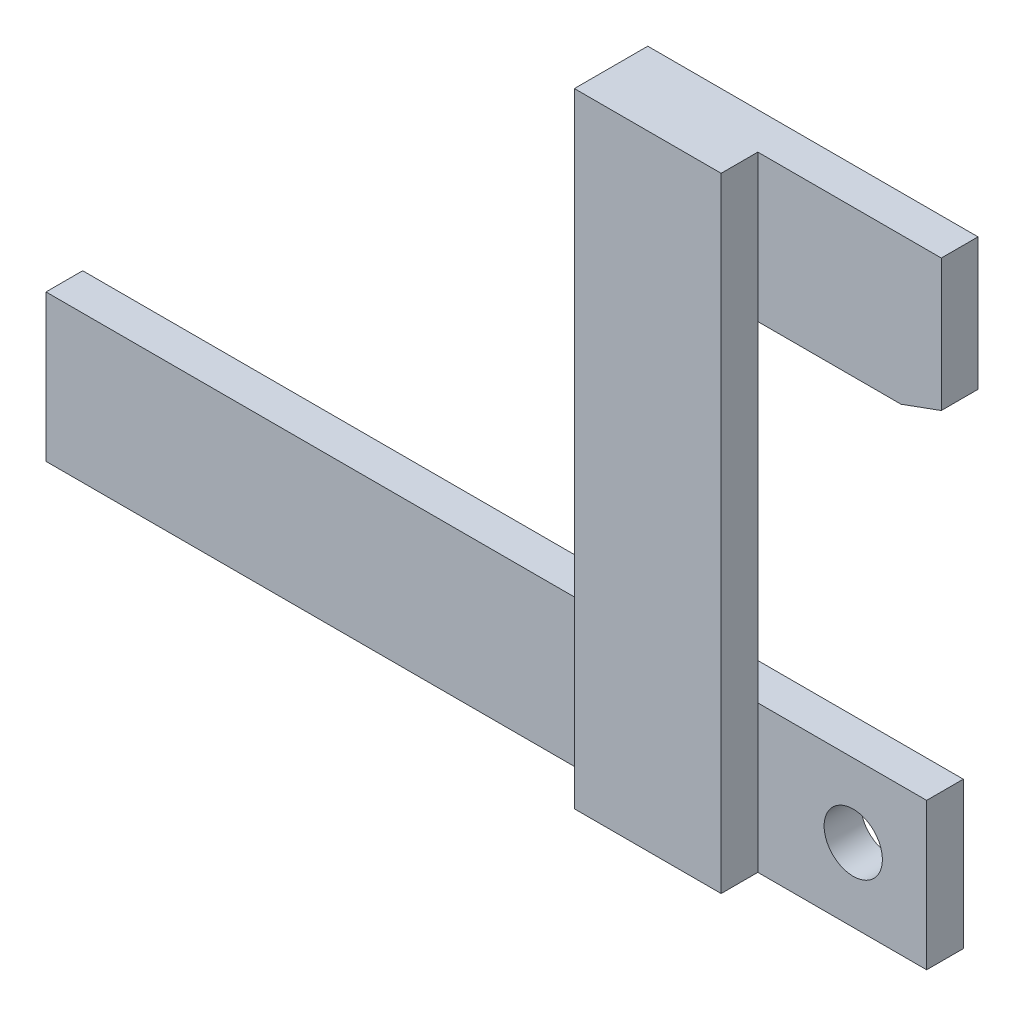
SolidWorks part; units mm, degrees
ref_plane "Front Plane" through (0, 0, 0) normal (0, 0, 1) x (1, 0, 0)
ref_plane "Top Plane" through (0, 0, 0) normal (0, 1, 0) x (1, 0, 0)
ref_plane "Right Plane" through (0, 0, 0) normal (1, 0, 0) x (0, 0, -1)
sketch "Sketch1" plane through (0, 0, 0) normal (0, 0, 1) x (1, 0, 0)
  line L1 (-76.2, -12.7) -> (76.2, -12.7)
  line L2 (-76.2, -12.7) -> (-76.2, 12.7)
  line L3 (-76.2, 12.7) -> (76.2, 12.7)
  line L4 (76.2, -12.7) -> (76.2, 12.7)
  line L5 (-76.2, -12.7) -> (76.2, 12.7) construction
  line L6 (-76.2, 12.7) -> (76.2, -12.7) construction
  point P0 (0, 0)
  dimension "D1" = 25.4
  dimension "D2" = 152.4
extrude "Extrude1" add sketch "Sketch1" along normal blind 6.35
sketch "Sketch2" plane through (0, 0, 6.35) normal (0, 0, 1) x (1, 0, 0)
  line L0 (-76.2, -12.7) -> (76.2, -12.7) construction
  line L1 (46.99, -12.7) -> (21.59, -12.7)
  line L2 (46.99, -12.7) -> (46.99, 95.25)
  line L3 (46.99, 95.25) -> (21.59, 95.25)
  line L4 (21.59, -12.7) -> (21.59, 95.25)
  line L5 (76.2, -12.7) -> (76.2, 12.7) construction
  dimension "D1" = 25.4
  dimension "D2" = 107.95
  dimension "D3" = 29.21
extrude "Extrude2" add sketch "Sketch2" along normal blind 6.35
sketch "Sketch3" plane through (0, 0, 6.35) normal (0, 0, -1) x (-1, 0, 0)
  line L0 (-46.99, 95.25) -> (-21.59, 95.25) construction
  line L1 (-21.59, 95.25) -> (-78.74, 95.25)
  line L2 (-21.59, 95.25) -> (-21.59, 69.85)
  line L3 (-21.59, 69.85) -> (-78.74, 69.85)
  line L4 (-78.74, 95.25) -> (-78.74, 69.85)
  line L6 (-21.59, 95.25) -> (-21.59, 12.7) construction
  dimension "D1" = 25.4
  dimension "D2" = 57.15
extrude "Extrude3" add sketch "Sketch3" along normal blind 6.35
chamfer "Chamfer1" distance 2.54 angle 70 1 edges at (78.74, 69.85, 3.175)
sketch "Sketch4" plane through (0, 0, 6.35) normal (0, 0, 1) x (1, 0, 0)
  line L0 (76.2, 0) -> (63.5, 0) construction
  line L1 (76.2, -12.7) -> (76.2, 12.7) construction
  dimension "D1" = 12.7
hole_wizard "3/8 Clearance Hole1" positions "3DSketch1" profile "Sketch5" hole size "3/8" standard "Ansi Inch"
sketch3d "3DSketch1"
  point P0 (63.5, 0, 6.35)
sketch "Sketch5" plane through (63.5, 0, 6.35) normal (1, 0, 0) x (0, -1, 0)
  line L0 (0, 0) -> (0, 41.1295)
  line L1 (0, 41.1295) -> (5.0419, 38.1)
  line L2 (5.0419, 38.1) -> (5.0419, 0)
  line L5 (5.0419, 0) -> (0, 0)
  line L10 (0, 41.1295) -> (-5.0419, 38.1) construction
  line L11 (0, -6.35) -> (0, 107.95) construction
  dimension "Hole Dia." = 10.0838
  dimension "Hole Depth" = 38.1
  dimension "Drill Angle" = 118
